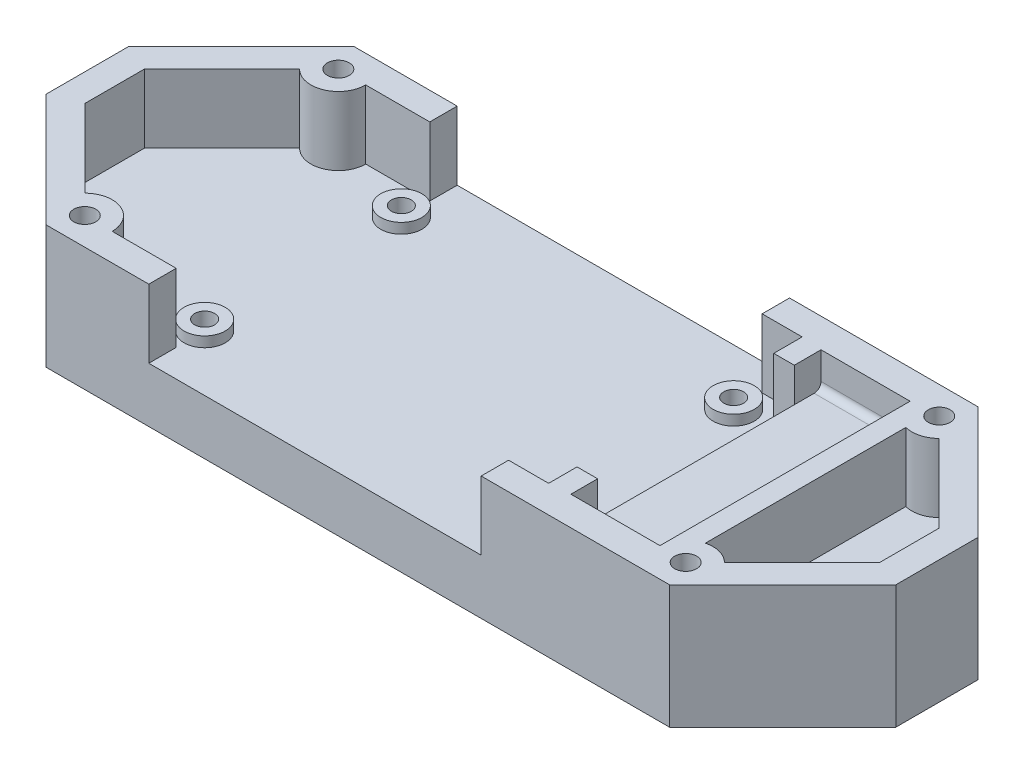
SolidWorks part; units mm, degrees
ref_plane "Front Plane" through (0, 0, 0) normal (0, 0, 1) x (1, 0, 0)
ref_plane "Top Plane" through (0, 0, 0) normal (0, 1, 0) x (1, 0, 0)
ref_plane "Right Plane" through (0, 0, 0) normal (1, 0, 0) x (0, 0, -1)
sketch "Sketch2" plane through (0, 0, 0) normal (0, 1, 0) x (1, 0, 0)
  line L0 (-62, 6) -> (-45.5, 22.5)
  line L1 (-45.5, -22.5) -> (45.5, -22.5)
  line L2 (-62, -6) -> (-62, 6)
  line L3 (-45.5, 22.5) -> (45.5, 22.5)
  line L4 (62, -6) -> (62, 6)
  line L5 (-62, -22.5) -> (62, 22.5) construction
  line L6 (-62, 22.5) -> (62, -22.5) construction
  line L7 (45.5, 22.5) -> (62, 6)
  line L8 (45.5, -22.5) -> (62, -6)
  line L9 (-62, -6) -> (-45.5, -22.5)
  point P0 (0, 0)
  dimension "D1" = 45
  dimension "D2" = 124
extrude "Boss-Extrude1" add sketch "Sketch2" along normal blind 8
sketch "Sketch5" plane through (0, 8, 0) normal (0, 1, 0) x (1, 0, 0)
  line L8 (-62, 6) -> (-62, -6)
  line L9 (-62, -6) -> (-45.5, -22.5)
  line L10 (-45.5, -22.5) -> (45.5, -22.5)
  line L11 (45.5, -22.5) -> (62, -6)
  line L12 (62, -6) -> (62, 6)
  line L13 (62, 6) -> (45.5, 22.5)
  line L14 (45.5, 22.5) -> (-45.5, 22.5)
  line L15 (-45.5, 22.5) -> (-62, 6)
  line L16 (-62, 6) -> (-62, -6)
  line L17 (-62, -6) -> (-45.5, -22.5)
  line L18 (-45.5, -22.5) -> (45.5, -22.5)
  line L19 (45.5, -22.5) -> (62, -6)
  line L20 (62, -6) -> (62, 6)
  line L21 (62, 6) -> (45.5, 22.5)
  line L22 (45.5, 22.5) -> (-45.5, 22.5)
  line L23 (-45.5, 22.5) -> (-62, 6)
  line L56 (-58, 4.3431) -> (-58, -4.3431)
  line L57 (-58, -4.3431) -> (-43.8431, -18.5)
  line L58 (-43.8431, -18.5) -> (43.8431, -18.5)
  line L59 (43.8431, -18.5) -> (58, -4.3431)
  line L60 (58, -4.3431) -> (58, 4.3431)
  line L61 (58, 4.3431) -> (43.8431, 18.5)
  line L62 (43.8431, 18.5) -> (-43.8431, 18.5)
  line L63 (-43.8431, 18.5) -> (-58, 4.3431)
  line L64 (-58, 4.3431) -> (-58, -4.3431)
  line L65 (-58, -4.3431) -> (-46.6716, -15.6716)
  line L66 (-39.8431, -18.5) -> (39.8431, -18.5)
  line L67 (46.6716, -15.6716) -> (58, -4.3431)
  line L68 (58, -4.3431) -> (58, 4.3431)
  line L69 (58, 4.3431) -> (46.6716, 15.6716)
  line L70 (39.8431, 18.5) -> (-39.8431, 18.5)
  line L71 (-46.6716, 15.6716) -> (-58, 4.3431)
  arc A0 (-46.6716, 15.6716) -> (-39.8431, 18.5) centre (-43.8431, 18.5) ccw
  arc A11 (39.8431, 18.5) -> (46.6716, 15.6716) centre (43.8431, 18.5) ccw
  arc A12 (46.6716, -15.6716) -> (39.8431, -18.5) centre (43.8431, -18.5) ccw
  arc A14 (-39.8431, -18.5) -> (-46.6716, -15.6716) centre (-43.8431, -18.5) ccw
  dimension "D3" = 4
  dimension "D1" = 0
  dimension "D2" = 4
extrude "Boss-Extrude2" add sketch "Sketch5" along normal blind 10
sketch "Sketch6" plane through (0, 8, 0) normal (0, 1, 0) x (1, 0, 0)
  line L1 (-30.5, -14.35) -> (18, -14.35) construction
  line L2 (-30.5, -14.35) -> (-30.5, 14.35) construction
  line L3 (-30.5, 14.35) -> (18, 14.35) construction
  line L4 (18, -14.35) -> (18, 14.35) construction
  line L5 (-30.5, -14.35) -> (18, 14.35) construction
  line L6 (-30.5, 14.35) -> (18, -14.35) construction
  line L7 (58, -4.3431) -> (58, 4.3431) construction
  circle A0 centre (18, 14.35) radius 3
  circle A1 centre (-30.5, 14.35) radius 3
  circle A2 centre (-30.5, -14.35) radius 3
  circle A3 centre (18, -14.35) radius 3
  point P0 (-6.25, 0)
  dimension "D4" = 6
  dimension "D1" = 48.5
  dimension "D2" = 28.7
  dimension "D3" = 40
extrude "Boss-Extrude3" add sketch "Sketch6" along normal blind 1.5
sketch "Sketch7" plane through (0, 8, 0) normal (0, 1, 0) x (1, 0, 0)
  line L1 (-30.5, 22.5) -> (18, 22.5)
  line L2 (-30.5, 22.5) -> (-30.5, 18.5)
  line L3 (-30.5, 18.5) -> (18, 18.5)
  line L4 (18, 22.5) -> (18, 18.5)
  line L7 (-30.5, -18.5) -> (18, -18.5)
  line L8 (-30.5, -18.5) -> (-30.5, -22.5)
  line L9 (-30.5, -22.5) -> (18, -22.5)
  line L10 (18, -18.5) -> (18, -22.5)
  line L12 (45.5, 22.5) -> (-45.5, 22.5) construction
  line L13 (-39.8431, -18.5) -> (39.8431, -18.5) construction
  point P16 (-30.5, 14.35)
  point P17 (18, 14.35)
  point P19 (0, 0)
extrude "Cut-Extrude3" cut sketch "Sketch7" along normal through all
sketch "Sketch8" plane through (0, 8, 0) normal (0, 1, 0) x (1, 0, 0)
  line L0 (23.8431, 18.5) -> (23.8431, -18.5)
  line L1 (26.8431, -18.25) -> (39.8431, -18.25)
  line L2 (26.8431, -18.25) -> (26.8431, 18.25)
  line L3 (26.8431, 18.25) -> (39.8431, 18.25)
  line L4 (39.8431, -18.25) -> (39.8431, 18.25)
  line L5 (26.8431, -18.25) -> (39.8431, 18.25) construction
  line L6 (26.8431, 18.25) -> (39.8431, -18.25) construction
  line L7 (42.8431, 14.627) -> (42.8431, -14.627)
  line L22 (39.8431, 18.5) -> (18, 18.5)
  line L23 (18, 18.5) -> (18, 22.5)
  line L24 (18, 22.5) -> (-30.5, 22.5)
  line L25 (-30.5, 22.5) -> (-30.5, 18.5)
  line L26 (-30.5, 18.5) -> (-39.8431, 18.5)
  line L27 (-46.6716, 15.6716) -> (-58, 4.3431)
  line L28 (-58, 4.3431) -> (-58, -4.3431)
  line L29 (-58, -4.3431) -> (-46.6716, -15.6716)
  line L30 (-39.8431, -18.5) -> (-30.5, -18.5)
  line L31 (-30.5, -18.5) -> (-30.5, -22.5)
  line L32 (-30.5, -22.5) -> (18, -22.5)
  line L33 (18, -22.5) -> (18, -18.5)
  line L34 (18, -18.5) -> (39.8431, -18.5)
  line L35 (46.6716, -15.6716) -> (58, -4.3431)
  line L36 (58, -4.3431) -> (58, 4.3431)
  line L37 (58, 4.3431) -> (46.6716, 15.6716)
  line L38 (39.8431, 18.5) -> (23.8431, 18.5)
  line L50 (23.8431, -18.5) -> (39.8431, -18.5)
  arc A4 (-46.6716, 15.6716) -> (-39.8431, 18.5) centre (-43.8431, 18.5) ccw
  arc A5 (-39.8431, -18.5) -> (-46.6716, -15.6716) centre (-43.8431, -18.5) ccw
  arc A6 (46.6716, -15.6716) -> (39.8431, -18.5) centre (43.8431, -18.5) ccw
  arc A7 (39.8431, 18.5) -> (46.6716, 15.6716) centre (43.8431, 18.5) ccw
  arc A10 (42.8431, -14.627) -> (39.8431, -18.5) centre (43.8431, -18.5) ccw
  arc A11 (39.8431, 18.5) -> (42.8431, 14.627) centre (43.8431, 18.5) ccw
  point P0 (33.3431, 0)
  dimension "D1" = 13
  dimension "D2" = 36.5
  dimension "D4" = 3
  dimension "D5" = 3
  dimension "D3" = 0
extrude "Boss-Extrude4" add sketch "Sketch8" along normal through all
sketch "Sketch9" plane through (0, 8, 0) normal (0, 1, 0) x (1, 0, 0)
  line L0 (23.8431, 18.5) -> (23.8431, -18.5) construction
  line L1 (23.8431, 14.35) -> (26.8431, 14.35)
  line L2 (23.8431, 14.35) -> (23.8431, -14.35)
  line L3 (23.8431, -14.35) -> (26.8431, -14.35)
  line L4 (26.8431, 14.35) -> (26.8431, -14.35)
  line L5 (26.8431, 18.25) -> (26.8431, -18.25) construction
  point P8 (18, 14.35)
  point P9 (18, -14.35)
extrude "Cut-Extrude4" cut sketch "Sketch9" along normal through all
sketch "Sketch10" plane through (0, 18, 0) normal (0, 1, 0) x (1, 0, 0)
  circle A0 centre (-43.8431, 18.5) radius 1.6
  circle A1 centre (43.8431, 18.5) radius 1.6
  circle A2 centre (43.8431, -18.5) radius 1.6
  circle A3 centre (-43.8431, -18.5) radius 1.6
  dimension "D1" = 3.2
extrude "Cut-Extrude5" cut sketch "Sketch10" against normal through all
sketch "Sketch11" plane through (0, 0, 0) normal (0, -1, 0) x (1, 0, 0)
  circle A0 centre (-43.8431, 18.5) radius 3
  circle A1 centre (43.8431, 18.5) radius 3
  circle A2 centre (43.8431, -18.5) radius 3
  circle A3 centre (-43.8431, -18.5) radius 3
  dimension "D1" = 6
extrude "Cut-Extrude6" cut sketch "Sketch11" against normal offset from surface (14 mm away) 4 up to face at (-43.8431, 18, 20.1)
sketch "Sketch12" plane through (0, 9.5, 0) normal (0, 1, 0) x (1, 0, 0)
  circle A0 centre (-30.5, 14.35) radius 1.45
  circle A1 centre (18, 14.35) radius 1.45
  circle A2 centre (18, -14.35) radius 1.45
  circle A3 centre (-30.5, -14.35) radius 1.45
  dimension "D1" = 2.9
extrude "Cut-Extrude7" cut sketch "Sketch12" against normal blind 6
sketch "Sketch13" plane through (0, 8, 0) normal (0, 1, 0) x (1, 0, 0)
  line L1 (26.8431, 18.25) -> (39.8431, 18.25)
  line L2 (26.8431, 18.25) -> (26.8431, -18.25)
  line L3 (26.8431, -18.25) -> (39.8431, -18.25)
  line L4 (39.8431, 18.25) -> (39.8431, -18.25)
extrude "Boss-Extrude5" add sketch "Sketch13" along normal offset from surface (5 mm away) 5 up to face at (43.8431, 18, 20.1)
sketch "Sketch14" plane through (0, 0, 0) normal (0, -1, 0) x (1, 0, 0)
  line L0 (-13.435, 13.435) -> (0, 0) construction
  line L1 (0, 0) -> (0, 19) construction
  circle A0 centre (0, 0) radius 19 construction
  circle A1 centre (-13.435, 13.435) radius 2
  circle A2 centre (13.435, 13.435) radius 2
  circle A3 centre (13.435, -13.435) radius 2
  circle A4 centre (-13.435, -13.435) radius 2
  point P14 (0, 0)
  dimension "D2" = 4
  dimension "D3" = 38
  dimension "D4" = 45
  dimension "D1" = 4
extrude "Cut-Extrude8" cut sketch "Sketch14" against normal blind 5
fillet "Fillet1" radius 1 2 edges at (33.3431, 13, 18.25) (33.3431, 13, -18.25)
